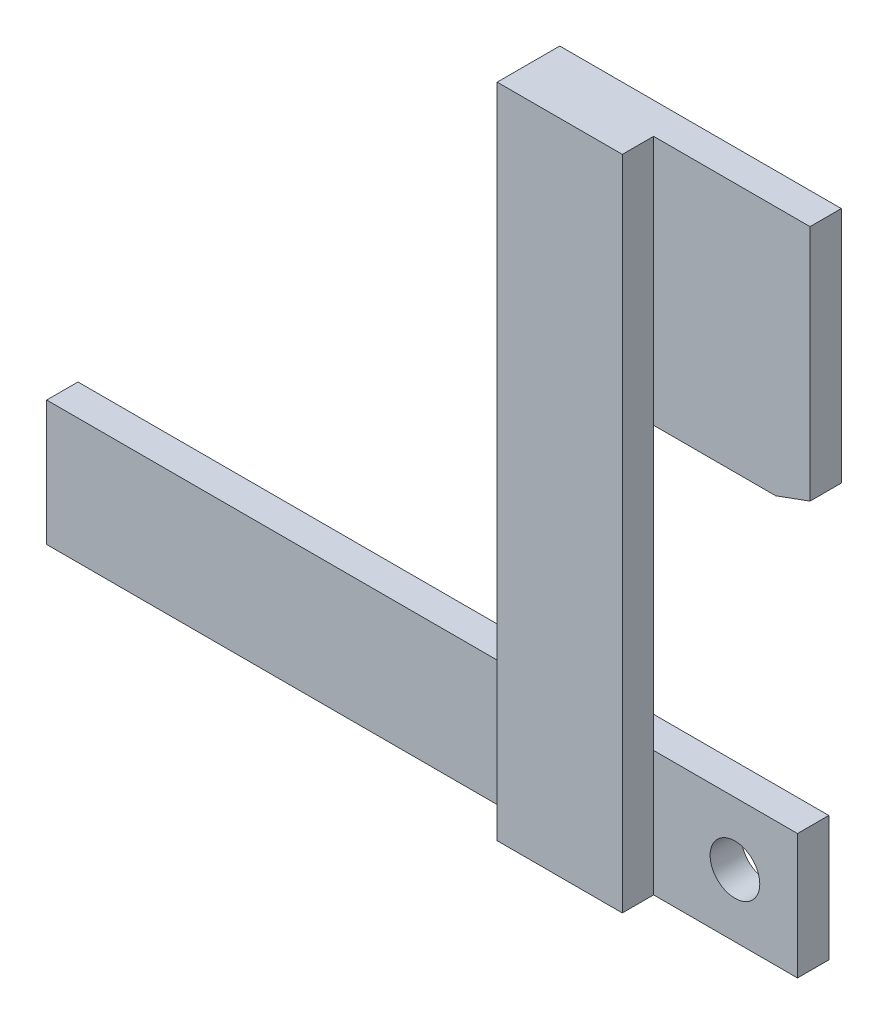
SolidWorks part; units mm, degrees
ref_plane "Front Plane" through (0, 0, 0) normal (0, 0, 1) x (1, 0, 0)
ref_plane "Top Plane" through (0, 0, 0) normal (0, 1, 0) x (1, 0, 0)
ref_plane "Right Plane" through (0, 0, 0) normal (1, 0, 0) x (0, 0, -1)
sketch "Sketch1" plane through (0, 0, 0) normal (0, 0, 1) x (1, 0, 0)
  line L1 (-76.2, -12.7) -> (76.2, -12.7)
  line L2 (-76.2, -12.7) -> (-76.2, 12.7)
  line L3 (-76.2, 12.7) -> (76.2, 12.7)
  line L4 (76.2, -12.7) -> (76.2, 12.7)
  line L5 (-76.2, -12.7) -> (76.2, 12.7) construction
  line L6 (-76.2, 12.7) -> (76.2, -12.7) construction
  point P0 (0, 0)
  dimension "D1" = 25.4
  dimension "D2" = 152.4
extrude "Extrude1" add sketch "Sketch1" along normal blind 6.35
sketch "Sketch2" plane through (0, 0, 6.35) normal (0, 0, 1) x (1, 0, 0)
  line L0 (-76.2, -12.7) -> (76.2, -12.7) construction
  line L1 (46.99, -12.7) -> (21.59, -12.7)
  line L2 (46.99, -12.7) -> (46.99, 120.65)
  line L3 (46.99, 120.65) -> (21.59, 120.65)
  line L4 (21.59, -12.7) -> (21.59, 120.65)
  line L5 (76.2, -12.7) -> (76.2, 12.7) construction
  dimension "D1" = 25.4
  dimension "D2" = 133.35
  dimension "D3" = 29.21
extrude "Extrude2" add sketch "Sketch2" along normal blind 6.35
sketch "Sketch3" plane through (0, 0, 6.35) normal (0, 0, -1) x (-1, 0, 0)
  line L0 (-46.99, 120.65) -> (-21.59, 120.65) construction
  line L1 (-21.59, 120.65) -> (-78.74, 120.65)
  line L2 (-21.59, 120.65) -> (-21.59, 69.85)
  line L3 (-21.59, 69.85) -> (-78.74, 69.85)
  line L4 (-78.74, 120.65) -> (-78.74, 69.85)
  line L6 (-21.59, 120.65) -> (-21.59, 12.7) construction
  dimension "D1" = 50.8
  dimension "D2" = 57.15
extrude "Extrude3" add sketch "Sketch3" along normal blind 6.35
chamfer "Chamfer1" distance 2.54 angle 70 1 edges at (78.74, 69.85, 3.175)
sketch "Sketch4" plane through (0, 0, 6.35) normal (0, 0, 1) x (1, 0, 0)
  line L0 (76.2, 0) -> (63.5, 0) construction
  line L1 (76.2, -12.7) -> (76.2, 12.7) construction
  dimension "D1" = 12.7
hole_wizard "3/8 Clearance Hole1" positions "3DSketch1" profile "Sketch5" hole size "3/8" standard "Ansi Inch"
sketch3d "3DSketch1"
  point P0 (63.5, 0, 6.35)
sketch "Sketch5" plane through (63.5, 0, 6.35) normal (1, 0, 0) x (0, -1, 0)
  line L0 (0, 0) -> (0, 41.1295)
  line L1 (0, 41.1295) -> (5.0419, 38.1)
  line L2 (5.0419, 38.1) -> (5.0419, 0)
  line L5 (5.0419, 0) -> (0, 0)
  line L10 (0, 41.1295) -> (-5.0419, 38.1) construction
  line L11 (0, -6.35) -> (0, 107.95) construction
  dimension "Hole Dia." = 10.0838
  dimension "Hole Depth" = 38.1
  dimension "Drill Angle" = 118
